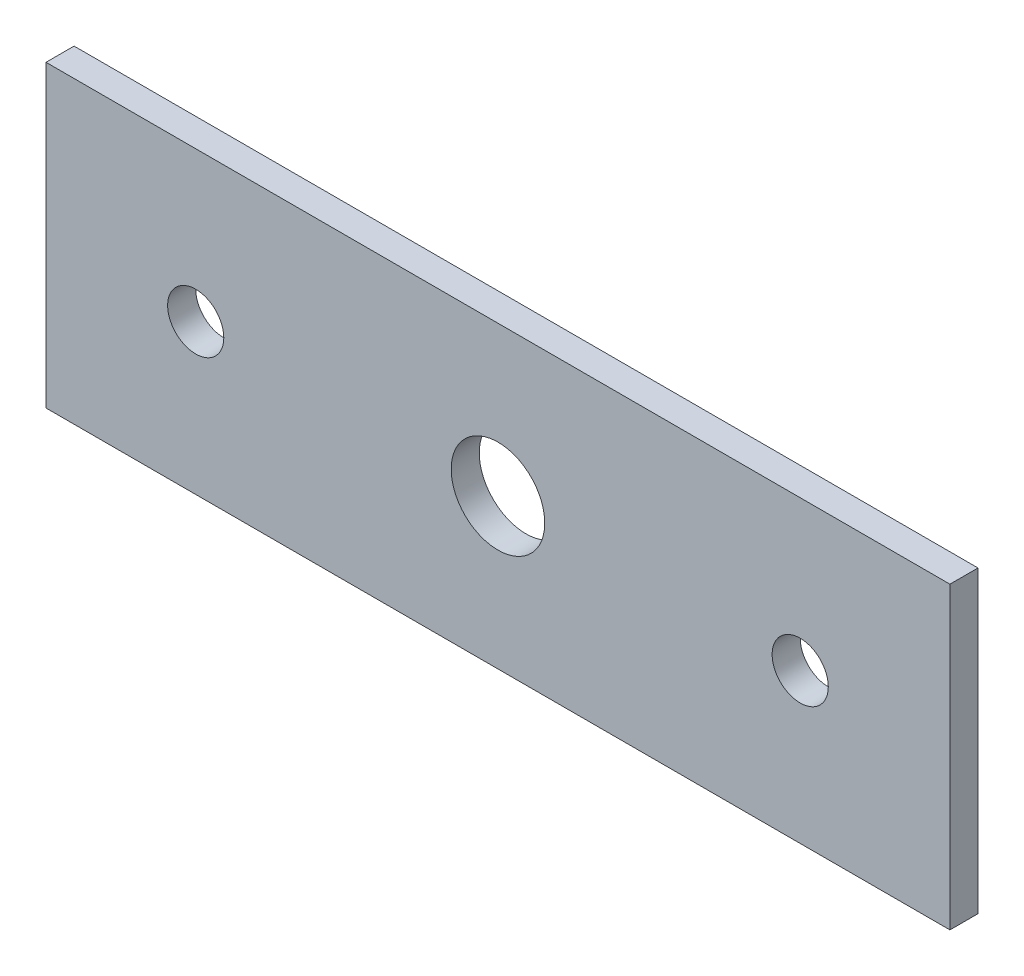
SolidWorks part; units mm, degrees
ref_plane "Plan de face" through (0, 0, 0) normal (0, 0, 1) x (1, 0, 0)
ref_plane "Plan de dessus" through (0, 0, 0) normal (0, 1, 0) x (1, 0, 0)
ref_plane "Plan de droite" through (0, 0, 0) normal (1, 0, 0) x (0, 0, -1)
sketch "Sketch1" plane through (0, 0, 0) normal (0, 0, 1) x (1, 0, 0)
  line L1 (-19.8825, 16.6713) -> (76.7175, 16.6713)
  line L2 (-19.8825, 16.6713) -> (-19.8825, -15.3287)
  line L3 (-19.8825, -15.3287) -> (76.7175, -15.3287)
  line L4 (76.7175, 16.6713) -> (76.7175, -15.3287)
  dimension "D1" = 32
  dimension "D2" = 96.6
extrude "Boss-Extrude1" add sketch "Sketch1" along normal blind 3
sketch "Sketch2" plane through (0, 0, 3) normal (0, 0, 1) x (1, 0, 0)
  line L0 (-19.8825, 16.6713) -> (-19.8825, -15.3287) construction
  line L1 (76.7175, 16.6713) -> (-19.8825, 16.6713) construction
  line L2 (76.7175, -15.3287) -> (76.7175, 16.6713) construction
  line L3 (-19.8825, -15.3287) -> (76.7175, -15.3287) construction
  circle A0 centre (-3.8825, 0.6713) radius 3
  circle A1 centre (60.7175, 0.6713) radius 3
  circle A2 centre (28.4175, 0.6713) radius 5
  point P12 (-19.8825, 0.6713)
  dimension "D1" = 6
  dimension "D4" = 16
  dimension "D6" = 6
  dimension "D7" = 48.3
  dimension "D2" = 16
  dimension "D3" = 16
  dimension "D5" = 16
  dimension "D8" = 16
extrude "Cut-Extrude1" cut sketch "Sketch2" against normal through all
